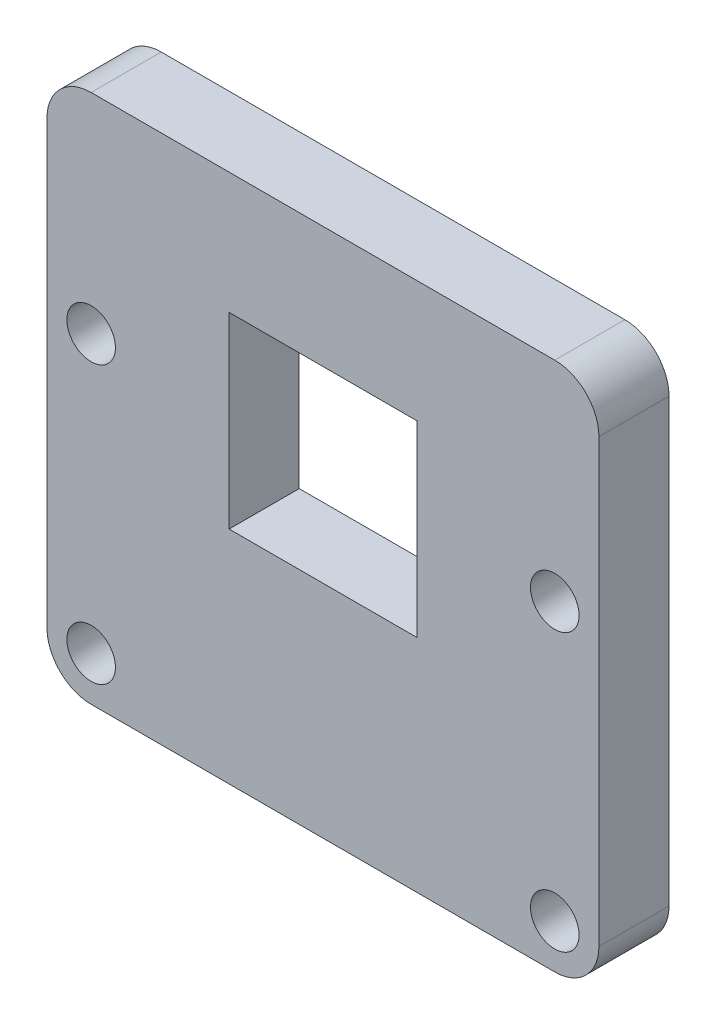
SolidWorks part; units mm, degrees
ref_plane "Front Plane" through (0, 0, 0) normal (0, 0, 1) x (1, 0, 0)
ref_plane "Top Plane" through (0, 0, 0) normal (0, 1, 0) x (1, 0, 0)
ref_plane "Right Plane" through (0, 0, 0) normal (1, 0, 0) x (0, 0, -1)
sketch "Sketch1" plane through (0, 0, 0) normal (0, 0, 1) x (1, 0, 0)
  line L1 (-10.7053, 7.0715) -> (10.2947, 7.0715)
  line L2 (-12.7053, 5.0715) -> (-12.7053, -14.9285)
  line L3 (-10.7053, -16.9285) -> (10.2947, -16.9285)
  line L4 (12.2947, 5.0715) -> (12.2947, -14.9285)
  line L5 (-4.4553, 1.5715) -> (4.0447, 1.5715)
  line L6 (-4.4553, 1.5715) -> (-4.4553, -6.9285)
  line L7 (-4.4553, -6.9285) -> (4.0447, -6.9285)
  line L8 (4.0447, 1.5715) -> (4.0447, -6.9285)
  circle A0 centre (-10.7053, -14.9285) radius 1.1
  circle A1 centre (-10.7053, -2.3905) radius 1.1
  circle A2 centre (10.2947, -2.3905) radius 1.1
  circle A3 centre (10.2947, -14.9285) radius 1.1
  arc A4 (-12.7053, -14.9285) -> (-10.7053, -16.9285) centre (-10.7053, -14.9285) ccw
  arc A5 (10.2947, -16.9285) -> (12.2947, -14.9285) centre (10.2947, -14.9285) ccw
  arc A6 (10.2947, 7.0715) -> (12.2947, 5.0715) centre (10.2947, 5.0715) cw
  arc A7 (-10.7053, 7.0715) -> (-12.7053, 5.0715) centre (-10.7053, 5.0715) ccw
  point P12 (-0.2053, 1.5715)
  point P17 (12.2947, -16.9285)
  point P24 (12.2947, 7.0715)
  point P27 (-12.7053, 7.0715)
  dimension "D3" = 2
  dimension "D11" = 2
  dimension "D1" = 25
  dimension "D2" = 24
  dimension "D4" = 2
  dimension "D5" = 2
  dimension "D6" = 9.462
  dimension "D7" = 8.5
  dimension "D8" = 8.5
  dimension "D9" = 12.5
  dimension "D10" = 5.5
extrude "Boss-Extrude1" add sketch "Sketch1" against normal blind 3.175
